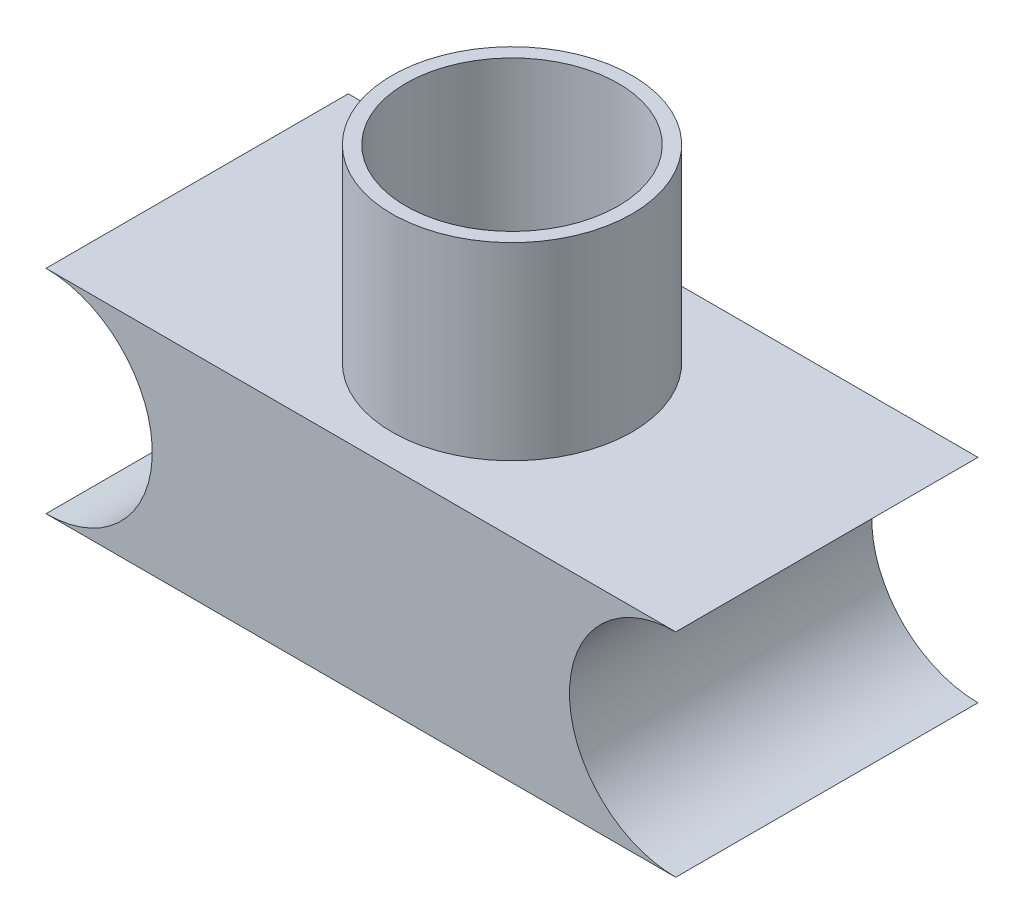
SolidWorks part; units mm, degrees
ref_plane "Front Plane" through (0, 0, 0) normal (0, 0, 1) x (1, 0, 0)
ref_plane "Top Plane" through (0, 0, 0) normal (0, 1, 0) x (1, 0, 0)
ref_plane "Right Plane" through (0, 0, 0) normal (1, 0, 0) x (0, 0, -1)
sketch "Sketch1" plane through (0, 0, 0) normal (0, 0, 1) x (1, 0, 0)
  line L0 (21.0344, 0) -> (-21.0344, 0) construction
  line L3 (-31.75, 10.7156) -> (31.75, 10.7156)
  line L4 (31.75, -10.7156) -> (-31.75, -10.7156)
  arc A0 (-31.75, -10.7156) -> (-31.75, 10.7156) centre (-31.75, 0) ccw
  arc A2 (31.75, 10.7156) -> (31.75, -10.7156) centre (31.75, 0) ccw
  point P4 (0, 0)
  point P9 (-31.75, 0)
  point P11 (31.75, 0)
  dimension "D1" = 21.4312
  dimension "D2" = 21.4312
  dimension "D3" = 63.5
  dimension "D4" = 21.4312
extrude "Boss-Extrude2" add sketch "Sketch1" along normal mid plane 30.48
sketch "Sketch3" plane through (0, 10.7156, 0) normal (0, 1, 0) x (1, 0, 0)
  circle A0 centre (0, 0) radius 12.0999
  circle A1 centre (0, 0) radius 10.7156
  dimension "D1" = 24.1998
  dimension "D2" = 21.4312
extrude "Boss-Extrude3" add sketch "Sketch3" along normal blind 19.05 contours A0 A1
ref_plane "Plane1" through (-31.75, 0, 0) normal (-1, 0, 0) x (0, 0, 1)
sketch "Sketch4" plane through (-31.75, 0, 0) normal (-1, 0, 0) x (0, 0, 1)
  line L0 (15.24, 0) -> (-15.24, 0) construction
  line L1 (-15.24, 10.7156) -> (-15.24, -10.7156) construction
  point P6 (0, 0)
sketch "Sketch5" plane through (0, 10.7156, 0) normal (0, 1, 0) x (1, 0, 0)
  point P0 (0, 0)
